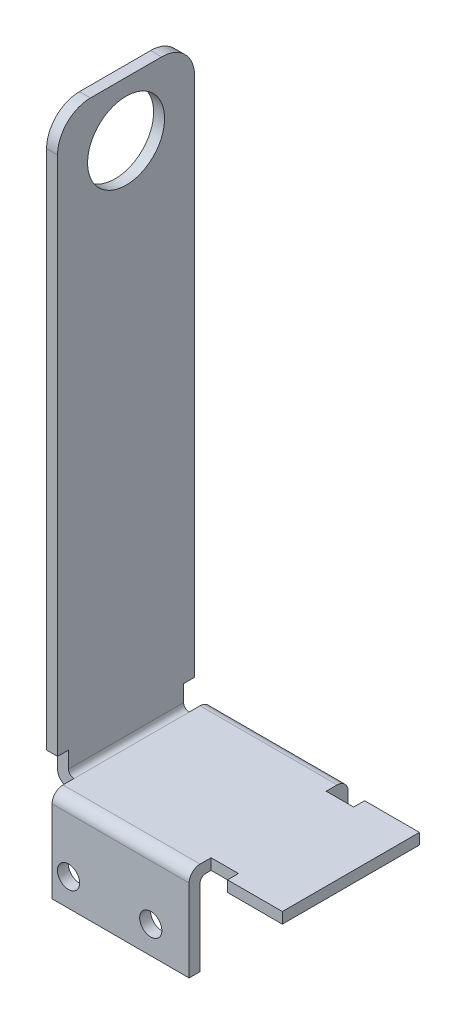
SolidWorks part; units mm, degrees
material "AISI 304"
ref_plane "Front Plane" through (0, 0, 0) normal (0, 0, 1) x (1, 0, 0)
ref_plane "Top Plane" through (0, 0, 0) normal (0, 1, 0) x (1, 0, 0)
ref_plane "Right Plane" through (0, 0, 0) normal (1, 0, 0) x (0, 0, -1)
sketch "Sketch1" plane through (0, 0, 0) normal (0, 1, 0) x (1, 0, 0)
  line L1 (-12.5, 12.5) -> (12.5, 12.5)
  line L2 (-12.5, 12.5) -> (-12.5, -12.5)
  line L3 (-12.5, -12.5) -> (12.5, -12.5)
  line L4 (12.5, 12.5) -> (12.5, -12.5)
  line L5 (-12.5, 12.5) -> (12.5, -12.5) construction
  line L6 (-12.5, -12.5) -> (12.5, 12.5) construction
  point P0 (0, 0)
  dimension "D1" = 25
  dimension "D2" = 25
extrude "Boss-Extrude1" add sketch "Sketch1" along normal blind 2
sketch "Sketch2" plane through (0, 0, 0) normal (0, -1, 0) x (1, 0, 0)
  line L0 (-12.5, 12.5) -> (-12.5, 14.5)
  line L1 (-12.5, 14.5) -> (12.5, 14.5)
  line L2 (12.5, 14.5) -> (12.5, 12.5)
  line L3 (12.5, 12.5) -> (-12.5, 12.5)
  line L4 (-28.5011, 0) -> (22.3998, 0) construction
  line L5 (12.5, -14.5) -> (12.5, -12.5)
  line L6 (-12.5, -14.5) -> (12.5, -14.5)
  line L7 (-12.5, -12.5) -> (-12.5, -14.5)
  line L8 (12.5, -12.5) -> (-12.5, -12.5)
  dimension "D1" = 2
extrude "Boss-Extrude2" add sketch "Sketch2" along normal blind 15 and the other way blind 2
sketch "Sketch3" plane through (0, 0, 14.5) normal (0, 0, 1) x (1, 0, 0)
  line L0 (-12.5, -15) -> (-12.5, 0) construction
  line L1 (-12.5, 0) -> (16.9538, 0) construction
  line L2 (-16.2457, -10) -> (16.454, -10) construction
  line L3 (12.5, -15) -> (-12.5, -15) construction
  circle A0 centre (-9.5, -10) radius 2.025
  circle A1 centre (5.5, -10) radius 2.025
  dimension "D2" = 4.05
  dimension "D3" = 4.05
  dimension "D1" = 5
  dimension "D4" = 15
  dimension "D5" = 3
extrude "Cut-Extrude1" cut sketch "Sketch3" against normal through all
fillet "Fillet1" radius 2 2 edges at (0, 2, 14.5) (0, 2, -14.5)
fillet "Fillet2" radius 1 2 edges at (0, 0, -12.5) (0, 0, 12.5)
sketch "Sketch4" plane through (-12.5, 0, 0) normal (-1, 0, 0) x (0, 0, 1)
  line L0 (-10.5, 0) -> (-10.5, 2)
  line L1 (-11.5, 0) -> (11.5, 0) construction
  line L2 (-12.5, 2) -> (12.5, 2) construction
  line L3 (-10.5, 2) -> (10.5, 2)
  line L4 (10.5, 2) -> (10.5, 0)
  line L5 (10.5, 0) -> (-10.5, 0)
  line L6 (-14.5, 0) -> (-14.5, -15) construction
  line L7 (14.5, 0) -> (14.5, -15) construction
  dimension "D1" = 4
  dimension "D2" = 4
extrude "Boss-Extrude3" add sketch "Sketch4" along normal blind 3
sketch "Sketch5" plane through (12.5, 0, 0) normal (1, 0, 0) x (0, 0, -1)
  line L0 (-10.5, 2) -> (-10.5, 0)
  line L1 (-12.5, 2) -> (12.5, 2) construction
  line L2 (-11.5, 0) -> (11.5, 0) construction
  line L3 (-10.5, 0) -> (10.5, 0)
  line L4 (10.5, 0) -> (10.5, 2)
  line L5 (10.5, 2) -> (-10.5, 2)
  line L6 (-14.5, 0) -> (-14.5, -15) construction
  line L7 (14.5, 0) -> (14.5, -15) construction
  dimension "D1" = 4
  dimension "D2" = 4
extrude "Boss-Extrude4" add sketch "Sketch5" along normal blind 15
sketch "Sketch6" plane through (0, 0, 10.5) normal (0, 0, 1) x (1, 0, 0)
  line L0 (27.5, 2) -> (27.5, 0)
  line L1 (27.5, 0) -> (17.5, 0)
  line L2 (27.5, 0) -> (12.5, 0) construction
  line L3 (17.5, 0) -> (17.5, 2)
  line L4 (27.5, 2) -> (12.5, 2) construction
  line L5 (17.5, 2) -> (27.5, 2)
  dimension "D1" = 10
extrude "Boss-Extrude5" add sketch "Sketch6" along normal blind 15 and the other way blind 36
sketch "Sketch7" plane through (0, 2, 0) normal (0, 1, 0) x (1, 0, 0)
  line L0 (-15.5, 20.5) -> (-13.5, 20.5)
  line L2 (-13.5, 20.5) -> (-13.5, -20.5)
  line L4 (-13.5, -20.5) -> (-15.5, -20.5)
  line L5 (-15.5, -20.5) -> (-15.5, 20.5)
  line L6 (-12.5, 12.5) -> (-12.5, 10.5) construction
  line L7 (-15.5, 10.5) -> (-12.5, 10.5) construction
  line L8 (-15.5, -10.5) -> (-12.5, -10.5) construction
  dimension "D1" = 3
  dimension "D2" = 2
  dimension "D3" = 10
  dimension "D4" = 10
extrude "Boss-Extrude6" add sketch "Sketch7" along normal blind 105
sketch "Sketch8" plane through (-13.5, 0, 0) normal (1, 0, 0) x (0, 0, -1)
  line L0 (-20.5, 6) -> (-10.5, 6)
  line L1 (-20.5, 107) -> (-20.5, 2) construction
  line L2 (-10.5, 6) -> (-10.5, 2)
  line L3 (-10.5, 2) -> (-20.5, 2)
  line L4 (-20.5, 2) -> (-20.5, 6)
  line L5 (0, -2.4971) -> (0, 10.2374) construction
  line L6 (10.5, 2) -> (20.5, 2)
  line L7 (10.5, 6) -> (10.5, 2)
  line L8 (20.5, 6) -> (10.5, 6)
  line L9 (20.5, 2) -> (20.5, 6)
  dimension "D1" = 4
extrude "Cut-Extrude2" cut sketch "Sketch8" against normal through all
fillet "Fillet3" radius 1 1 edges at (-13.5, 2, 0)
fillet "Fillet4" radius 2 1 edges at (-15.5, 0, 0)
sketch "Sketch12" plane through (-15.5, 0, 0) normal (-1, 0, 0) x (0, 0, 1)
  line L0 (0, -9.8641) -> (0, 116.677) construction
  line L1 (-20.5, 107) -> (20.5, 107) construction
  circle A0 centre (0, 97) radius 7.025
  dimension "D1" = 14.05
  dimension "D2" = 10
extrude "Cut-Extrude4" cut sketch "Sketch12" against normal through all
sketch "Sketch13" plane through (-15.5, 0, 0) normal (-1, 0, 0) x (0, 0, 1)
  line L0 (0, 105.678) -> (0, -7.4302) construction
  line L1 (-20.5, 107) -> (-20.5, 52)
  line L2 (-20.5, 107) -> (-20.5, 6) construction
  line L3 (-20.5, 52) -> (-12.5, 60)
  line L4 (-12.5, 60) -> (-12.5, 107)
  line L5 (-20.5, 107) -> (20.5, 107) construction
  line L6 (-12.5, 107) -> (-20.5, 107)
  line L7 (12.5, 60) -> (12.5, 107)
  line L8 (20.5, 52) -> (12.5, 60)
  line L9 (20.5, 107) -> (20.5, 52)
  line L10 (12.5, 107) -> (20.5, 107)
  dimension "D1" = 55
  dimension "D2" = 8
  dimension "D3" = 45
extrude "Cut-Extrude5" cut sketch "Sketch13" against normal through all
fillet "Fillet7" radius 6 2 edges at (-14.5, 107, -12.5) (-14.5, 107, 12.5)
fillet "Fillet8" radius 6 2 edges at (-14.5, 6, -20.5) (-14.5, 6, 20.5)
sketch "Sketch14" plane through (0, 2, 0) normal (0, 1, 0) x (1, 0, 0)
  line L0 (17.5, 25.5) -> (27.5, 25.5)
  line L1 (27.5, 25.5) -> (27.5, 20.5)
  line L2 (27.5, 25.5) -> (27.5, -25.5) construction
  line L3 (27.5, 20.5) -> (17.5, 20.5)
  line L4 (17.5, 25.5) -> (17.5, 10.5) construction
  line L5 (17.5, 20.5) -> (17.5, 25.5)
  line L6 (0, 0) -> (37.7541, 0) construction
  line L7 (27.5, -20.5) -> (17.5, -20.5)
  line L8 (27.5, -25.5) -> (27.5, -20.5)
  line L9 (17.5, -25.5) -> (27.5, -25.5)
  line L10 (17.5, -20.5) -> (17.5, -25.5)
  dimension "D1" = 5
extrude "Cut-Extrude6" cut sketch "Sketch14" against normal through all
sketch "Sketch15" plane through (-13.5, 0, 0) normal (1, 0, 0) x (0, 0, -1)
  line L0 (-12.5, 60) -> (-12.5, 6)
  line L1 (-10.5, 6) -> (-14.5, 6) construction
  line L2 (-12.5, 6) -> (-27.5, 6)
  line L3 (-27.5, 6) -> (-27.5, 60)
  line L4 (-27.5, 60) -> (-12.5, 60)
  line L5 (0, 126.9222) -> (0, -5.8901) construction
  line L6 (27.5, 6) -> (27.5, 60)
  line L7 (12.5, 6) -> (27.5, 6)
  line L8 (12.5, 60) -> (12.5, 6)
  line L9 (27.5, 60) -> (12.5, 60)
  dimension "D1" = 15
extrude "Cut-Extrude7" cut sketch "Sketch15" against normal through all
sketch "Sketch16" plane through (0, 2, 0) normal (0, 1, 0) x (1, 0, 0)
  line L0 (17.5, -20.5) -> (17.5, -12.5)
  line L1 (17.5, -10.5) -> (17.5, -20.5) construction
  line L2 (17.5, -12.5) -> (27.5, -12.5)
  line L3 (27.5, 20.5) -> (27.5, -20.5) construction
  line L4 (27.5, -12.5) -> (27.5, -20.5)
  line L5 (27.5, -20.5) -> (17.5, -20.5)
  line L6 (0, 0) -> (33.5906, 0) construction
  line L7 (27.5, 12.5) -> (27.5, 20.5)
  line L8 (17.5, 12.5) -> (27.5, 12.5)
  line L9 (17.5, 20.5) -> (17.5, 12.5)
  line L10 (27.5, 20.5) -> (17.5, 20.5)
  dimension "D1" = 8
extrude "Cut-Extrude8" cut sketch "Sketch16" against normal blind 10
